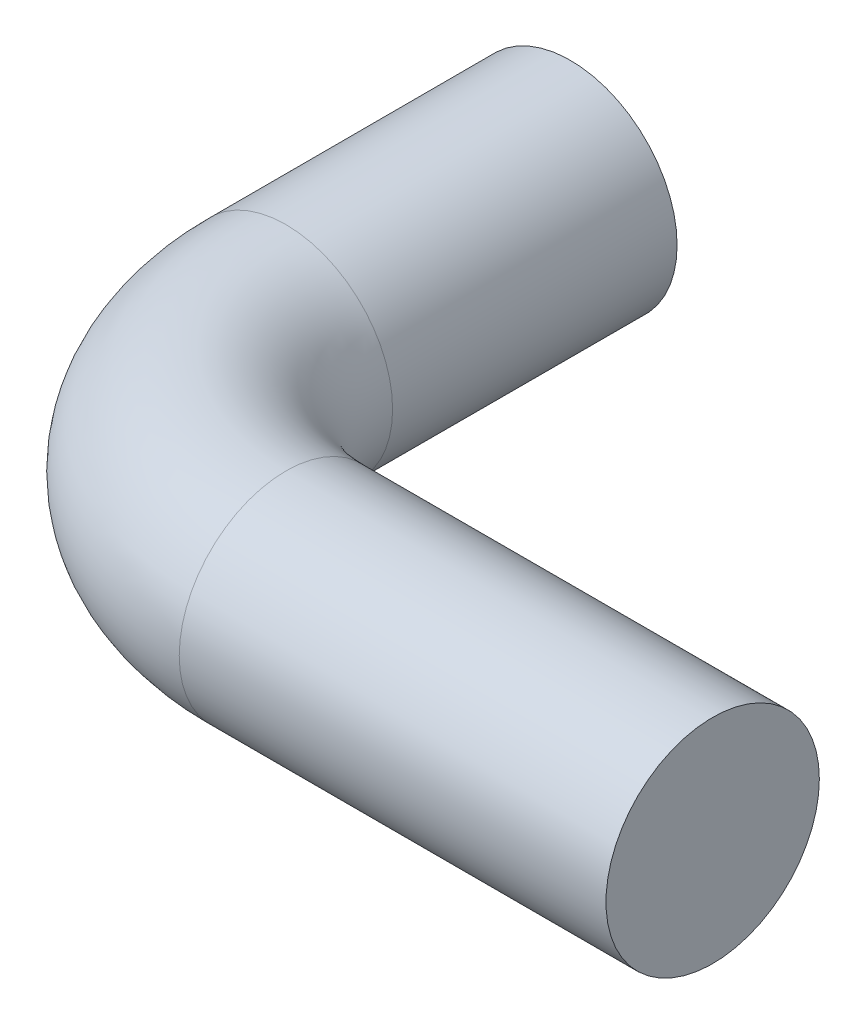
SolidWorks part; units mm, degrees
material "Plain Carbon Steel"
ref_plane "Front Plane" through (0, 0, 0) normal (0, 0, 1) x (1, 0, 0)
ref_plane "Top Plane" through (0, 0, 0) normal (0, 1, 0) x (1, 0, 0)
ref_plane "Right Plane" through (0, 0, 0) normal (1, 0, 0) x (0, 0, -1)
sketch "Sketch2" plane through (0, 0, 0) normal (0, 1, 0) x (1, 0, 0)
  line L0 (0, 0) -> (150, 0)
  line L1 (-75, 175) -> (-75, 75)
  arc A0 (-75, 75) -> (0, 0) centre (0, 75) ccw
  dimension "D1" = 150
  dimension "D2" = 75
  dimension "D3" = 75
  dimension "D4" = 100
sweep "Sweep1" add path "Sketch2" circular profile diameter 75 parameters "D3"=75
sketch "Sketch5" plane through (0, 0, -175) normal (0, 0, -1) x (-1, 0, 0)
  circle A0 centre (75, 0) radius 50
  circle A1 centre (75, 0) radius 37.5 construction
  dimension "D1" = 100
extrude "Boss-Extrude1" [suppressed] add sketch "Sketch5" against normal blind 10 contours A0
sketch "Sketch6" [suppressed] plane through (0, 0, -165) normal (0, 0, 1) x (1, 0, 0)
  circle A0 centre (-75, 0) radius 42.5
  circle A1 centre (-75, 0) radius 37.5 construction
  point P4 (-75, 42.5)
  point P8 (-32.5, 0)
  point P9 (-75, -42.5)
  point P10 (-117.5, 0)
  point P11 (-75, 0)
  dimension "D1" = 85
  dimension "D2" = 4
hole_wizard "Ø5.0mm Dowel Hole1" [suppressed] positions "Sketch7" profile "Sketch8" hole size "Ø5.0" standard "ANSI Metric"
sketch "Sketch7" [suppressed] plane through (0, 0, -165) normal (0, 0, 1) x (1, 0, 0)
  point P0 (-75, 42.5)
  point P3 (-32.5, 0)
  point P6 (-75, -42.5)
  point P9 (-117.5, 0)
sketch "Sketch8" plane through (-75, 42.5, -165) normal (1, 0, 0) x (0, -1, 0)
  line L0 (0, 0) -> (0, 10)
  line L1 (0, 10) -> (2.5, 10)
  line L2 (2.5, 10) -> (2.5, 0)
  line L5 (2.5, 0) -> (0, 0)
  line L11 (0, -6.35) -> (0, 107.95) construction
  dimension "Thru Hole Dia." = 5
  dimension "Thru Hole Depth" = 10
